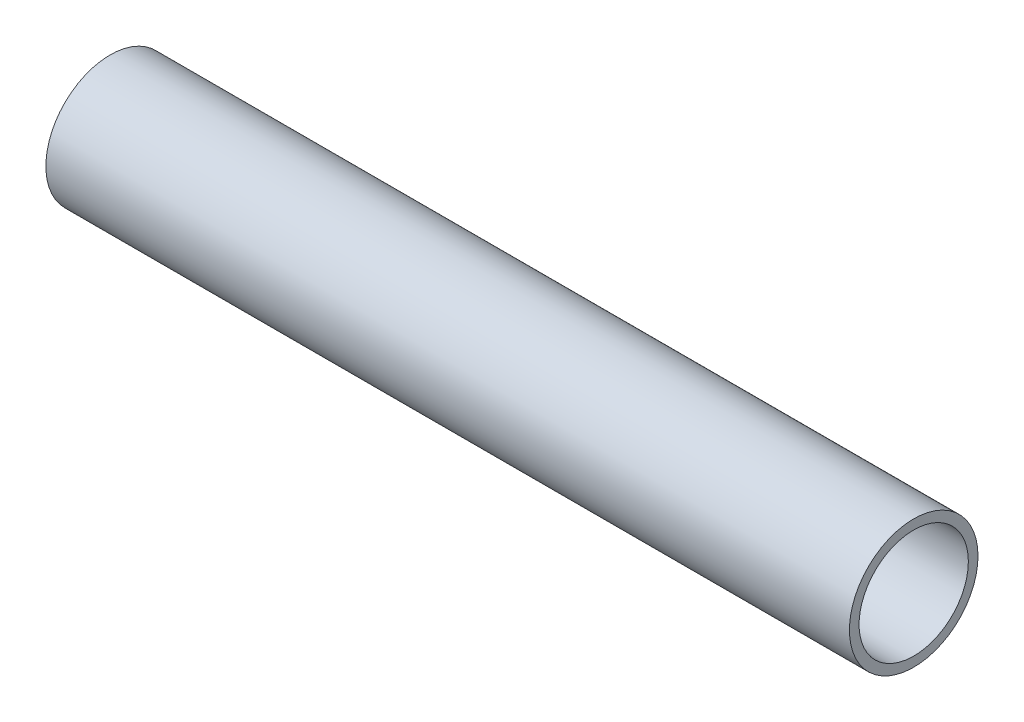
SolidWorks part; units mm, degrees
ref_plane "Front Plane" through (0, 0, 0) normal (0, 0, 1) x (1, 0, 0)
ref_plane "Top Plane" through (0, 0, 0) normal (0, 1, 0) x (1, 0, 0)
ref_plane "Right Plane" through (0, 0, 0) normal (1, 0, 0) x (0, 0, -1)
sketch "Sketch1" plane through (0, 0, 0) normal (1, 0, 0) x (0, 0, -1)
  circle A0 centre (0, 0) radius 2
  circle A1 centre (0, 0) radius 1.7
  dimension "D1" = 4
  dimension "D2" = 3.4
extrude "Boss-Extrude2" add sketch "Sketch1" along normal mid plane 25
